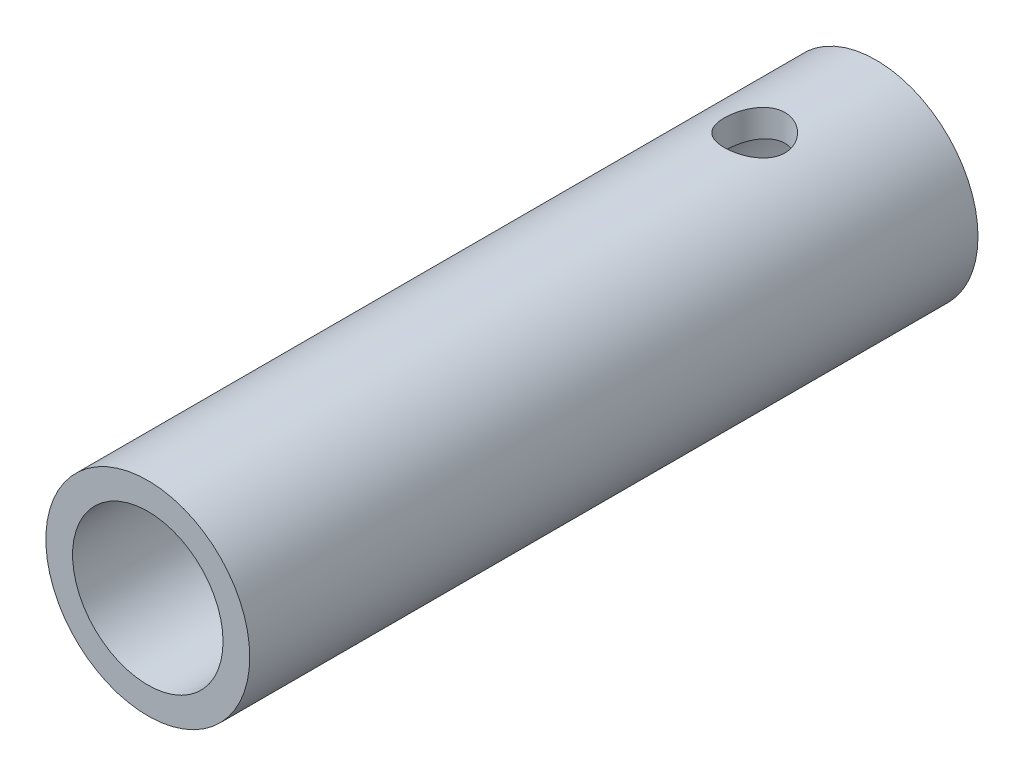
SolidWorks part; units mm, degrees
ref_plane "Front Plane" through (0, 0, 0) normal (0, 0, 1) x (1, 0, 0)
ref_plane "Top Plane" through (0, 0, 0) normal (0, 1, 0) x (1, 0, 0)
ref_plane "Right Plane" through (0, 0, 0) normal (1, 0, 0) x (0, 0, -1)
sketch "Sketch1" plane through (0, 0, 0) normal (0, 0, 1) x (1, 0, 0)
  circle A0 centre (0, 0) radius 10.668
  circle A1 centre (0, 0) radius 7.874
  dimension "D1" = 15.748
  dimension "D2" = 21.336
extrude "Boss-Extrude1" add sketch "Sketch1" along normal blind 76.2
sketch "Sketch3" plane through (0, 0, 0) normal (0, 1, 0) x (1, 0, 0)
  line L1 (7.874, 0) -> (-7.874, 0) construction
  circle A0 centre (0, -12.7) radius 3.175
  dimension "D1" = 12.7
extrude "Cut-Extrude1" cut sketch "Sketch3" along normal blind 26.9
